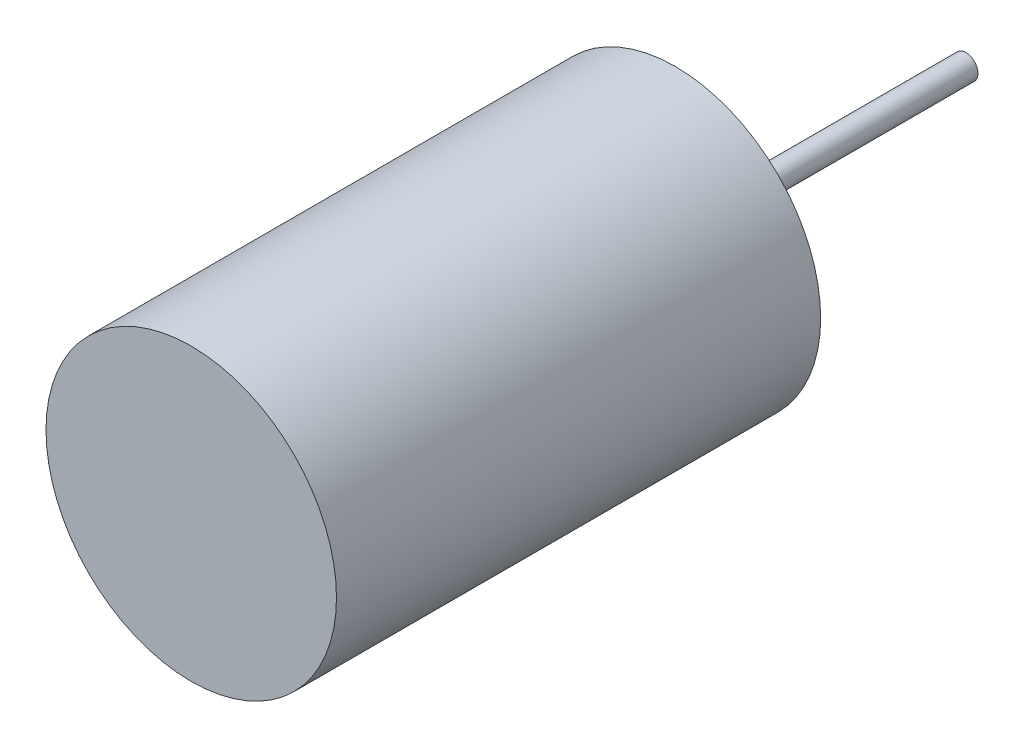
SolidWorks part; units mm, degrees
ref_plane "Front Plane" through (0, 0, 0) normal (0, 0, 1) x (1, 0, 0)
ref_plane "Top Plane" through (0, 0, 0) normal (0, 1, 0) x (1, 0, 0)
ref_plane "Right Plane" through (0, 0, 0) normal (1, 0, 0) x (0, 0, -1)
sketch "Sketch1" plane through (0, 0, 0) normal (0, 0, 1) x (1, 0, 0)
  circle A0 centre (0, 0) radius 3
  dimension "D1" = 6
extrude "Boss-Extrude1" add sketch "Sketch1" along normal blind 10
sketch "Sketch2" plane through (0, 0, 0) normal (0, 0, -1) x (-1, 0, 0)
  circle A0 centre (0, 0) radius 0.25
  dimension "D1" = 0.5
extrude "Boss-Extrude2" add sketch "Sketch2" along normal blind 6
